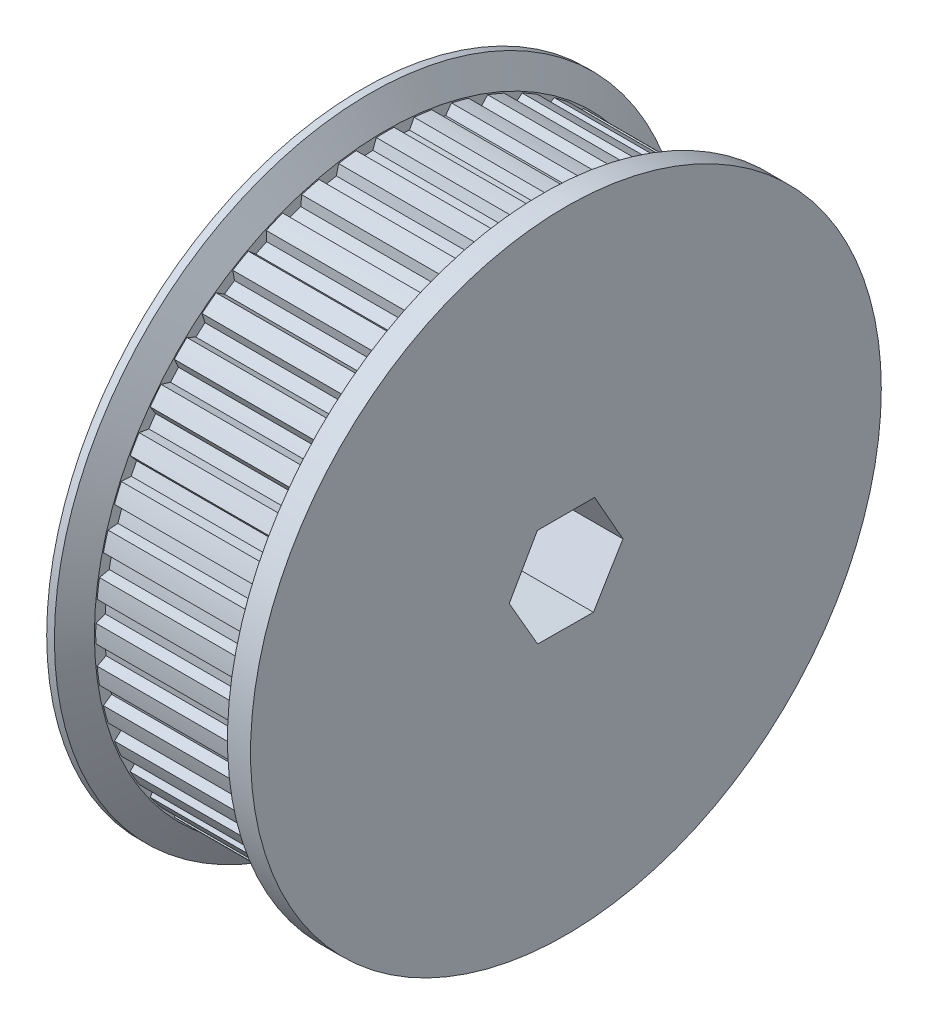
SolidWorks part; units mm, degrees
ref_plane "Front Plane" through (0, 0, 0) normal (0, 0, 1) x (1, 0, 0)
ref_plane "Top Plane" through (0, 0, 0) normal (0, 1, 0) x (1, 0, 0)
ref_plane "Right Plane" through (0, 0, 0) normal (1, 0, 0) x (0, 0, -1)
ref_plane "Plane1" through (0, 0, 0) normal (0, 0, -1) x (-1, 0, 0)
sketch "Sketch1" plane through (0, 0, 0) normal (0, 0, -1) x (-1, 0, 0)
  line L0 (-20.5, 37.625) -> (-20.5, 0)
  line L1 (-20.5, 0) -> (0, 0)
  line L2 (0, 0) -> (0, 37.625)
  line L3 (0, 37.625) -> (-20.5, 37.625)
  line L4 (-20.5, 0) -> (0, 0) construction
revolve "Revolve1" add sketch "Sketch1" angle 360 about L4
sketch "Sketch2" plane through (0, 0, 0) normal (-1, 0, 0) x (0, 0, 1)
  line L0 (-37.6072, 1.1569) -> (-36.3898, 1.6)
  line L1 (-36.2874, 3.1635) -> (-37.4365, 3.7617)
  arc A0 (-37.4365, 3.7617) -> (-37.6072, 1.1569) centre (0, 0) ccw
  arc A1 (-36.3898, 1.6) -> (-36.2874, 3.1635) centre (0, 0) cw
extrude "Cut-Extrude1" cut sketch "Sketch2" against normal through all
sketch "Sketch3" plane through (0, 0, 0) normal (-1, 0, 0) x (0, 0, 1)
  line L0 (-37.1345, 6.0557) -> (-35.8697, 6.3361)
  line L1 (-35.564, 7.8729) -> (-36.6252, 8.616)
  arc A0 (-36.6252, 8.616) -> (-37.1345, 6.0557) centre (0, 0) ccw
  arc A1 (-35.8697, 6.3361) -> (-35.564, 7.8729) centre (0, 0) cw
extrude "Cut-Extrude2" cut sketch "Sketch3" against normal through all
sketch "Sketch4" plane through (0, 0, 0) normal (-1, 0, 0) x (0, 0, 1)
  line L0 (-36.0263, 10.851) -> (-34.7358, 10.9639)
  line L1 (-34.2321, 12.4476) -> (-35.1873, 13.3228)
  arc A0 (-35.1873, 13.3228) -> (-36.0263, 10.851) centre (0, 0) ccw
  arc A1 (-34.7358, 10.9639) -> (-34.2321, 12.4476) centre (0, 0) cw
extrude "Cut-Extrude3" cut sketch "Sketch4" against normal through all
sketch "Sketch5" plane through (0, 0, 0) normal (-1, 0, 0) x (0, 0, 1)
  line L0 (-34.3018, 15.4605) -> (-33.0075, 15.404)
  line L1 (-32.3145, 16.8093) -> (-33.1473, 17.8017)
  arc A0 (-33.1473, 17.8017) -> (-34.3018, 15.4605) centre (0, 0) ccw
  arc A1 (-33.0075, 15.404) -> (-32.3145, 16.8093) centre (0, 0) cw
extrude "Cut-Extrude4" cut sketch "Sketch5" against normal through all
sketch "Sketch6" plane through (0, 0, 0) normal (-1, 0, 0) x (0, 0, 1)
  line L0 (-31.9903, 19.8055) -> (-30.7145, 19.5806)
  line L1 (-29.844, 20.8834) -> (-30.5401, 21.976)
  arc A0 (-30.5401, 21.976) -> (-31.9903, 19.8055) centre (0, 0) ccw
  arc A1 (-30.7145, 19.5806) -> (-29.844, 20.8834) centre (0, 0) cw
extrude "Cut-Extrude5" cut sketch "Sketch6" against normal through all
sketch "Sketch7" plane through (0, 0, 0) normal (-1, 0, 0) x (0, 0, 1)
  line L0 (-29.1315, 23.8117) -> (-27.896, 23.4221)
  line L1 (-26.8629, 24.6001) -> (-27.4104, 25.7743)
  arc A0 (-27.4104, 25.7743) -> (-29.1315, 23.8117) centre (0, 0) ccw
  arc A1 (-27.896, 23.4221) -> (-26.8629, 24.6001) centre (0, 0) cw
extrude "Cut-Extrude6" cut sketch "Sketch7" against normal through all
sketch "Sketch8" plane through (0, 0, 0) normal (-1, 0, 0) x (0, 0, 1)
  line L0 (-25.7743, 27.4104) -> (-24.6001, 26.8629)
  line L1 (-23.4221, 27.896) -> (-23.8117, 29.1315)
  arc A0 (-23.8117, 29.1315) -> (-25.7743, 27.4104) centre (0, 0) ccw
  arc A1 (-24.6001, 26.8629) -> (-23.4221, 27.896) centre (0, 0) cw
extrude "Cut-Extrude7" cut sketch "Sketch8" against normal through all
sketch "Sketch9" plane through (0, 0, 0) normal (-1, 0, 0) x (0, 0, 1)
  line L0 (-21.976, 30.5401) -> (-20.8834, 29.844)
  line L1 (-19.5806, 30.7145) -> (-19.8055, 31.9903)
  arc A0 (-19.8055, 31.9903) -> (-21.976, 30.5401) centre (0, 0) ccw
  arc A1 (-20.8834, 29.844) -> (-19.5806, 30.7145) centre (0, 0) cw
extrude "Cut-Extrude8" cut sketch "Sketch9" against normal through all
sketch "Sketch10" plane through (0, 0, 0) normal (-1, 0, 0) x (0, 0, 1)
  line L0 (-17.8017, 33.1473) -> (-16.8093, 32.3145)
  line L1 (-15.404, 33.0075) -> (-15.4605, 34.3018)
  arc A0 (-15.4605, 34.3018) -> (-17.8017, 33.1473) centre (0, 0) ccw
  arc A1 (-16.8093, 32.3145) -> (-15.404, 33.0075) centre (0, 0) cw
extrude "Cut-Extrude9" cut sketch "Sketch10" against normal through all
sketch "Sketch11" plane through (0, 0, 0) normal (-1, 0, 0) x (0, 0, 1)
  line L0 (-13.3228, 35.1873) -> (-12.4476, 34.2321)
  line L1 (-10.9639, 34.7358) -> (-10.851, 36.0263)
  arc A0 (-10.851, 36.0263) -> (-13.3228, 35.1873) centre (0, 0) ccw
  arc A1 (-12.4476, 34.2321) -> (-10.9639, 34.7358) centre (0, 0) cw
extrude "Cut-Extrude10" cut sketch "Sketch11" against normal through all
sketch "Sketch12" plane through (0, 0, 0) normal (-1, 0, 0) x (0, 0, 1)
  line L0 (-8.616, 36.6252) -> (-7.8729, 35.564)
  line L1 (-6.3361, 35.8697) -> (-6.0557, 37.1345)
  arc A0 (-6.0557, 37.1345) -> (-8.616, 36.6252) centre (0, 0) ccw
  arc A1 (-7.8729, 35.564) -> (-6.3361, 35.8697) centre (0, 0) cw
extrude "Cut-Extrude11" cut sketch "Sketch12" against normal through all
sketch "Sketch13" plane through (0, 0, 0) normal (-1, 0, 0) x (0, 0, 1)
  line L0 (-3.7617, 37.4365) -> (-3.1635, 36.2874)
  line L1 (-1.6, 36.3898) -> (-1.1569, 37.6072)
  arc A0 (-1.1569, 37.6072) -> (-3.7617, 37.4365) centre (0, 0) ccw
  arc A1 (-3.1635, 36.2874) -> (-1.6, 36.3898) centre (0, 0) cw
extrude "Cut-Extrude12" cut sketch "Sketch13" against normal through all
sketch "Sketch14" plane through (0, 0, 0) normal (-1, 0, 0) x (0, 0, 1)
  line L0 (1.1569, 37.6072) -> (1.6, 36.3898)
  line L1 (3.1635, 36.2874) -> (3.7617, 37.4365)
  arc A0 (3.7617, 37.4365) -> (1.1569, 37.6072) centre (0, 0) ccw
  arc A1 (1.6, 36.3898) -> (3.1635, 36.2874) centre (0, 0) cw
extrude "Cut-Extrude13" cut sketch "Sketch14" against normal through all
sketch "Sketch15" plane through (0, 0, 0) normal (-1, 0, 0) x (0, 0, 1)
  line L0 (6.0557, 37.1345) -> (6.3361, 35.8697)
  line L1 (7.8729, 35.564) -> (8.616, 36.6252)
  arc A0 (8.616, 36.6252) -> (6.0557, 37.1345) centre (0, 0) ccw
  arc A1 (6.3361, 35.8697) -> (7.8729, 35.564) centre (0, 0) cw
extrude "Cut-Extrude14" cut sketch "Sketch15" against normal through all
sketch "Sketch16" plane through (0, 0, 0) normal (-1, 0, 0) x (0, 0, 1)
  line L0 (10.851, 36.0263) -> (10.9639, 34.7358)
  line L1 (12.4476, 34.2321) -> (13.3228, 35.1873)
  arc A0 (13.3228, 35.1873) -> (10.851, 36.0263) centre (0, 0) ccw
  arc A1 (10.9639, 34.7358) -> (12.4476, 34.2321) centre (0, 0) cw
extrude "Cut-Extrude15" cut sketch "Sketch16" against normal through all
sketch "Sketch17" plane through (0, 0, 0) normal (-1, 0, 0) x (0, 0, 1)
  line L0 (15.4605, 34.3018) -> (15.404, 33.0075)
  line L1 (16.8093, 32.3145) -> (17.8017, 33.1473)
  arc A0 (17.8017, 33.1473) -> (15.4605, 34.3018) centre (0, 0) ccw
  arc A1 (15.404, 33.0075) -> (16.8093, 32.3145) centre (0, 0) cw
extrude "Cut-Extrude16" cut sketch "Sketch17" against normal through all
sketch "Sketch18" plane through (0, 0, 0) normal (-1, 0, 0) x (0, 0, 1)
  line L0 (19.8055, 31.9903) -> (19.5806, 30.7145)
  line L1 (20.8834, 29.844) -> (21.976, 30.5401)
  arc A0 (21.976, 30.5401) -> (19.8055, 31.9903) centre (0, 0) ccw
  arc A1 (19.5806, 30.7145) -> (20.8834, 29.844) centre (0, 0) cw
extrude "Cut-Extrude17" cut sketch "Sketch18" against normal through all
sketch "Sketch19" plane through (0, 0, 0) normal (-1, 0, 0) x (0, 0, 1)
  line L0 (23.8117, 29.1315) -> (23.4221, 27.896)
  line L1 (24.6001, 26.8629) -> (25.7743, 27.4104)
  arc A0 (25.7743, 27.4104) -> (23.8117, 29.1315) centre (0, 0) ccw
  arc A1 (23.4221, 27.896) -> (24.6001, 26.8629) centre (0, 0) cw
extrude "Cut-Extrude18" cut sketch "Sketch19" against normal through all
sketch "Sketch20" plane through (0, 0, 0) normal (-1, 0, 0) x (0, 0, 1)
  line L0 (27.4104, 25.7743) -> (26.8629, 24.6001)
  line L1 (27.896, 23.4221) -> (29.1315, 23.8117)
  arc A0 (29.1315, 23.8117) -> (27.4104, 25.7743) centre (0, 0) ccw
  arc A1 (26.8629, 24.6001) -> (27.896, 23.4221) centre (0, 0) cw
extrude "Cut-Extrude19" cut sketch "Sketch20" against normal through all
sketch "Sketch21" plane through (0, 0, 0) normal (-1, 0, 0) x (0, 0, 1)
  line L0 (30.5401, 21.976) -> (29.844, 20.8834)
  line L1 (30.7145, 19.5806) -> (31.9903, 19.8055)
  arc A0 (31.9903, 19.8055) -> (30.5401, 21.976) centre (0, 0) ccw
  arc A1 (29.844, 20.8834) -> (30.7145, 19.5806) centre (0, 0) cw
extrude "Cut-Extrude20" cut sketch "Sketch21" against normal through all
sketch "Sketch22" plane through (0, 0, 0) normal (-1, 0, 0) x (0, 0, 1)
  line L0 (33.1473, 17.8017) -> (32.3145, 16.8093)
  line L1 (33.0075, 15.404) -> (34.3018, 15.4605)
  arc A0 (34.3018, 15.4605) -> (33.1473, 17.8017) centre (0, 0) ccw
  arc A1 (32.3145, 16.8093) -> (33.0075, 15.404) centre (0, 0) cw
extrude "Cut-Extrude21" cut sketch "Sketch22" against normal through all
sketch "Sketch23" plane through (0, 0, 0) normal (-1, 0, 0) x (0, 0, 1)
  line L0 (35.1873, 13.3228) -> (34.2321, 12.4476)
  line L1 (34.7358, 10.9639) -> (36.0263, 10.851)
  arc A0 (36.0263, 10.851) -> (35.1873, 13.3228) centre (0, 0) ccw
  arc A1 (34.2321, 12.4476) -> (34.7358, 10.9639) centre (0, 0) cw
extrude "Cut-Extrude22" cut sketch "Sketch23" against normal through all
sketch "Sketch24" plane through (0, 0, 0) normal (-1, 0, 0) x (0, 0, 1)
  line L0 (36.6252, 8.616) -> (35.564, 7.8729)
  line L1 (35.8697, 6.3361) -> (37.1345, 6.0557)
  arc A0 (37.1345, 6.0557) -> (36.6252, 8.616) centre (0, 0) ccw
  arc A1 (35.564, 7.8729) -> (35.8697, 6.3361) centre (0, 0) cw
extrude "Cut-Extrude23" cut sketch "Sketch24" against normal through all
sketch "Sketch25" plane through (0, 0, 0) normal (-1, 0, 0) x (0, 0, 1)
  line L0 (37.4365, 3.7617) -> (36.2874, 3.1635)
  line L1 (36.3898, 1.6) -> (37.6072, 1.1569)
  arc A0 (37.6072, 1.1569) -> (37.4365, 3.7617) centre (0, 0) ccw
  arc A1 (36.2874, 3.1635) -> (36.3898, 1.6) centre (0, 0) cw
extrude "Cut-Extrude24" cut sketch "Sketch25" against normal through all
sketch "Sketch26" plane through (0, 0, 0) normal (-1, 0, 0) x (0, 0, 1)
  line L0 (37.6072, -1.1569) -> (36.3898, -1.6)
  line L1 (36.2874, -3.1635) -> (37.4365, -3.7617)
  arc A0 (37.4365, -3.7617) -> (37.6072, -1.1569) centre (0, 0) ccw
  arc A1 (36.3898, -1.6) -> (36.2874, -3.1635) centre (0, 0) cw
extrude "Cut-Extrude25" cut sketch "Sketch26" against normal through all
sketch "Sketch27" plane through (0, 0, 0) normal (-1, 0, 0) x (0, 0, 1)
  line L0 (37.1345, -6.0557) -> (35.8697, -6.3361)
  line L1 (35.564, -7.8729) -> (36.6252, -8.616)
  arc A0 (36.6252, -8.616) -> (37.1345, -6.0557) centre (0, 0) ccw
  arc A1 (35.8697, -6.3361) -> (35.564, -7.8729) centre (0, 0) cw
extrude "Cut-Extrude26" cut sketch "Sketch27" against normal through all
sketch "Sketch28" plane through (0, 0, 0) normal (-1, 0, 0) x (0, 0, 1)
  line L0 (36.0263, -10.851) -> (34.7358, -10.9639)
  line L1 (34.2321, -12.4476) -> (35.1873, -13.3228)
  arc A0 (35.1873, -13.3228) -> (36.0263, -10.851) centre (0, 0) ccw
  arc A1 (34.7358, -10.9639) -> (34.2321, -12.4476) centre (0, 0) cw
extrude "Cut-Extrude27" cut sketch "Sketch28" against normal through all
sketch "Sketch29" plane through (0, 0, 0) normal (-1, 0, 0) x (0, 0, 1)
  line L0 (34.3018, -15.4605) -> (33.0075, -15.404)
  line L1 (32.3145, -16.8093) -> (33.1473, -17.8017)
  arc A0 (33.1473, -17.8017) -> (34.3018, -15.4605) centre (0, 0) ccw
  arc A1 (33.0075, -15.404) -> (32.3145, -16.8093) centre (0, 0) cw
extrude "Cut-Extrude28" cut sketch "Sketch29" against normal through all
sketch "Sketch30" plane through (0, 0, 0) normal (-1, 0, 0) x (0, 0, 1)
  line L0 (31.9903, -19.8055) -> (30.7145, -19.5806)
  line L1 (29.844, -20.8834) -> (30.5401, -21.976)
  arc A0 (30.5401, -21.976) -> (31.9903, -19.8055) centre (0, 0) ccw
  arc A1 (30.7145, -19.5806) -> (29.844, -20.8834) centre (0, 0) cw
extrude "Cut-Extrude29" cut sketch "Sketch30" against normal through all
sketch "Sketch31" plane through (0, 0, 0) normal (-1, 0, 0) x (0, 0, 1)
  line L0 (29.1315, -23.8117) -> (27.896, -23.4221)
  line L1 (26.8629, -24.6001) -> (27.4104, -25.7743)
  arc A0 (27.4104, -25.7743) -> (29.1315, -23.8117) centre (0, 0) ccw
  arc A1 (27.896, -23.4221) -> (26.8629, -24.6001) centre (0, 0) cw
extrude "Cut-Extrude30" cut sketch "Sketch31" against normal through all
sketch "Sketch32" plane through (0, 0, 0) normal (-1, 0, 0) x (0, 0, 1)
  line L0 (25.7743, -27.4104) -> (24.6001, -26.8629)
  line L1 (23.4221, -27.896) -> (23.8117, -29.1315)
  arc A0 (23.8117, -29.1315) -> (25.7743, -27.4104) centre (0, 0) ccw
  arc A1 (24.6001, -26.8629) -> (23.4221, -27.896) centre (0, 0) cw
extrude "Cut-Extrude31" cut sketch "Sketch32" against normal through all
sketch "Sketch33" plane through (0, 0, 0) normal (-1, 0, 0) x (0, 0, 1)
  line L0 (21.976, -30.5401) -> (20.8834, -29.844)
  line L1 (19.5806, -30.7145) -> (19.8055, -31.9903)
  arc A0 (19.8055, -31.9903) -> (21.976, -30.5401) centre (0, 0) ccw
  arc A1 (20.8834, -29.844) -> (19.5806, -30.7145) centre (0, 0) cw
extrude "Cut-Extrude32" cut sketch "Sketch33" against normal through all
sketch "Sketch34" plane through (0, 0, 0) normal (-1, 0, 0) x (0, 0, 1)
  line L0 (17.8017, -33.1473) -> (16.8093, -32.3145)
  line L1 (15.404, -33.0075) -> (15.4605, -34.3018)
  arc A0 (15.4605, -34.3018) -> (17.8017, -33.1473) centre (0, 0) ccw
  arc A1 (16.8093, -32.3145) -> (15.404, -33.0075) centre (0, 0) cw
extrude "Cut-Extrude33" cut sketch "Sketch34" against normal through all
sketch "Sketch35" plane through (0, 0, 0) normal (-1, 0, 0) x (0, 0, 1)
  line L0 (13.3228, -35.1873) -> (12.4476, -34.2321)
  line L1 (10.9639, -34.7358) -> (10.851, -36.0263)
  arc A0 (10.851, -36.0263) -> (13.3228, -35.1873) centre (0, 0) ccw
  arc A1 (12.4476, -34.2321) -> (10.9639, -34.7358) centre (0, 0) cw
extrude "Cut-Extrude34" cut sketch "Sketch35" against normal through all
sketch "Sketch36" plane through (0, 0, 0) normal (-1, 0, 0) x (0, 0, 1)
  line L0 (8.616, -36.6252) -> (7.8729, -35.564)
  line L1 (6.3361, -35.8697) -> (6.0557, -37.1345)
  arc A0 (6.0557, -37.1345) -> (8.616, -36.6252) centre (0, 0) ccw
  arc A1 (7.8729, -35.564) -> (6.3361, -35.8697) centre (0, 0) cw
extrude "Cut-Extrude35" cut sketch "Sketch36" against normal through all
sketch "Sketch37" plane through (0, 0, 0) normal (-1, 0, 0) x (0, 0, 1)
  line L0 (3.7617, -37.4365) -> (3.1635, -36.2874)
  line L1 (1.6, -36.3898) -> (1.1569, -37.6072)
  arc A0 (1.1569, -37.6072) -> (3.7617, -37.4365) centre (0, 0) ccw
  arc A1 (3.1635, -36.2874) -> (1.6, -36.3898) centre (0, 0) cw
extrude "Cut-Extrude36" cut sketch "Sketch37" against normal through all
sketch "Sketch38" plane through (0, 0, 0) normal (-1, 0, 0) x (0, 0, 1)
  line L0 (-1.1569, -37.6072) -> (-1.6, -36.3898)
  line L1 (-3.1635, -36.2874) -> (-3.7617, -37.4365)
  arc A0 (-3.7617, -37.4365) -> (-1.1569, -37.6072) centre (0, 0) ccw
  arc A1 (-1.6, -36.3898) -> (-3.1635, -36.2874) centre (0, 0) cw
extrude "Cut-Extrude37" cut sketch "Sketch38" against normal through all
sketch "Sketch39" plane through (0, 0, 0) normal (-1, 0, 0) x (0, 0, 1)
  line L0 (-6.0557, -37.1345) -> (-6.3361, -35.8697)
  line L1 (-7.8729, -35.564) -> (-8.616, -36.6252)
  arc A0 (-8.616, -36.6252) -> (-6.0557, -37.1345) centre (0, 0) ccw
  arc A1 (-6.3361, -35.8697) -> (-7.8729, -35.564) centre (0, 0) cw
extrude "Cut-Extrude38" cut sketch "Sketch39" against normal through all
sketch "Sketch40" plane through (0, 0, 0) normal (-1, 0, 0) x (0, 0, 1)
  line L0 (-10.851, -36.0263) -> (-10.9639, -34.7358)
  line L1 (-12.4476, -34.2321) -> (-13.3228, -35.1873)
  arc A0 (-13.3228, -35.1873) -> (-10.851, -36.0263) centre (0, 0) ccw
  arc A1 (-10.9639, -34.7358) -> (-12.4476, -34.2321) centre (0, 0) cw
extrude "Cut-Extrude39" cut sketch "Sketch40" against normal through all
sketch "Sketch41" plane through (0, 0, 0) normal (-1, 0, 0) x (0, 0, 1)
  line L0 (-15.4605, -34.3018) -> (-15.404, -33.0075)
  line L1 (-16.8093, -32.3145) -> (-17.8017, -33.1473)
  arc A0 (-17.8017, -33.1473) -> (-15.4605, -34.3018) centre (0, 0) ccw
  arc A1 (-15.404, -33.0075) -> (-16.8093, -32.3145) centre (0, 0) cw
extrude "Cut-Extrude40" cut sketch "Sketch41" against normal through all
sketch "Sketch42" plane through (0, 0, 0) normal (-1, 0, 0) x (0, 0, 1)
  line L0 (-19.8055, -31.9903) -> (-19.5806, -30.7145)
  line L1 (-20.8834, -29.844) -> (-21.976, -30.5401)
  arc A0 (-21.976, -30.5401) -> (-19.8055, -31.9903) centre (0, 0) ccw
  arc A1 (-19.5806, -30.7145) -> (-20.8834, -29.844) centre (0, 0) cw
extrude "Cut-Extrude41" cut sketch "Sketch42" against normal through all
sketch "Sketch43" plane through (0, 0, 0) normal (-1, 0, 0) x (0, 0, 1)
  line L0 (-23.8117, -29.1315) -> (-23.4221, -27.896)
  line L1 (-24.6001, -26.8629) -> (-25.7743, -27.4104)
  arc A0 (-25.7743, -27.4104) -> (-23.8117, -29.1315) centre (0, 0) ccw
  arc A1 (-23.4221, -27.896) -> (-24.6001, -26.8629) centre (0, 0) cw
extrude "Cut-Extrude42" cut sketch "Sketch43" against normal through all
sketch "Sketch44" plane through (0, 0, 0) normal (-1, 0, 0) x (0, 0, 1)
  line L0 (-27.4104, -25.7743) -> (-26.8629, -24.6001)
  line L1 (-27.896, -23.4221) -> (-29.1315, -23.8117)
  arc A0 (-29.1315, -23.8117) -> (-27.4104, -25.7743) centre (0, 0) ccw
  arc A1 (-26.8629, -24.6001) -> (-27.896, -23.4221) centre (0, 0) cw
extrude "Cut-Extrude43" cut sketch "Sketch44" against normal through all
sketch "Sketch45" plane through (0, 0, 0) normal (-1, 0, 0) x (0, 0, 1)
  line L0 (-30.5401, -21.976) -> (-29.844, -20.8834)
  line L1 (-30.7145, -19.5806) -> (-31.9903, -19.8055)
  arc A0 (-31.9903, -19.8055) -> (-30.5401, -21.976) centre (0, 0) ccw
  arc A1 (-29.844, -20.8834) -> (-30.7145, -19.5806) centre (0, 0) cw
extrude "Cut-Extrude44" cut sketch "Sketch45" against normal through all
sketch "Sketch46" plane through (0, 0, 0) normal (-1, 0, 0) x (0, 0, 1)
  line L0 (-33.1473, -17.8017) -> (-32.3145, -16.8093)
  line L1 (-33.0075, -15.404) -> (-34.3018, -15.4605)
  arc A0 (-34.3018, -15.4605) -> (-33.1473, -17.8017) centre (0, 0) ccw
  arc A1 (-32.3145, -16.8093) -> (-33.0075, -15.404) centre (0, 0) cw
extrude "Cut-Extrude45" cut sketch "Sketch46" against normal through all
sketch "Sketch47" plane through (0, 0, 0) normal (-1, 0, 0) x (0, 0, 1)
  line L0 (-35.1873, -13.3228) -> (-34.2321, -12.4476)
  line L1 (-34.7358, -10.9639) -> (-36.0263, -10.851)
  arc A0 (-36.0263, -10.851) -> (-35.1873, -13.3228) centre (0, 0) ccw
  arc A1 (-34.2321, -12.4476) -> (-34.7358, -10.9639) centre (0, 0) cw
extrude "Cut-Extrude46" cut sketch "Sketch47" against normal through all
sketch "Sketch48" plane through (0, 0, 0) normal (-1, 0, 0) x (0, 0, 1)
  line L0 (-36.6252, -8.616) -> (-35.564, -7.8729)
  line L1 (-35.8697, -6.3361) -> (-37.1345, -6.0557)
  arc A0 (-37.1345, -6.0557) -> (-36.6252, -8.616) centre (0, 0) ccw
  arc A1 (-35.564, -7.8729) -> (-35.8697, -6.3361) centre (0, 0) cw
extrude "Cut-Extrude47" cut sketch "Sketch48" against normal through all
sketch "Sketch49" plane through (0, 0, 0) normal (-1, 0, 0) x (0, 0, 1)
  line L0 (-37.4365, -3.7617) -> (-36.2874, -3.1635)
  line L1 (-36.3898, -1.6) -> (-37.6072, -1.1569)
  arc A0 (-37.6072, -1.1569) -> (-37.4365, -3.7617) centre (0, 0) ccw
  arc A1 (-36.2874, -3.1635) -> (-36.3898, -1.6) centre (0, 0) cw
extrude "Cut-Extrude48" cut sketch "Sketch49" against normal through all
sketch "Sketch58" plane through (20.5, 0, 0) normal (1, 0, 0) x (0, 0, -1)
  circle A0 centre (0, 0) radius 41
  point P2 (-31.0745, 14.1125)
  point P3 (-1.6281, 5.6786)
  point P4 (-34.6409, 1.5043)
extrude "Boss-Extrude2" add sketch "Sketch58" along normal blind 3 contours A0
sketch "Sketch60" plane through (0, 0, 0) normal (-1, 0, 0) x (0, 0, 1)
  circle A0 centre (0, 0) radius 41
  point P2 (-62.6107, 23.318)
  point P3 (-33.1643, 14.8841)
  point P4 (-66.177, 10.7098)
extrude "Boss-Extrude4" add sketch "Sketch60" along normal blind 3
chamfer "Chamfer1" distance 3.2 distance2 2 1 edges at (0, 0, 41)
sketch "Sketch54" plane through (0, 0, 0) normal (1, 0, 0) x (0, 0, -1)
  line L0 (-3.7161, 6.4008) -> (-7.3705, 0)
  line L1 (-7.3705, 0) -> (-3.6748, -6.4008)
  line L2 (-3.6748, -6.4008) -> (3.5818, -6.4534)
  line L3 (3.5818, -6.4534) -> (7.4109, -0.1072)
  line L4 (7.4109, -0.1072) -> (3.7368, 6.4008)
  line L5 (3.7368, 6.4008) -> (-3.7161, 6.4008)
extrude "Cut-Extrude49" cut sketch "Sketch54" against normal through all both and the other way through all
